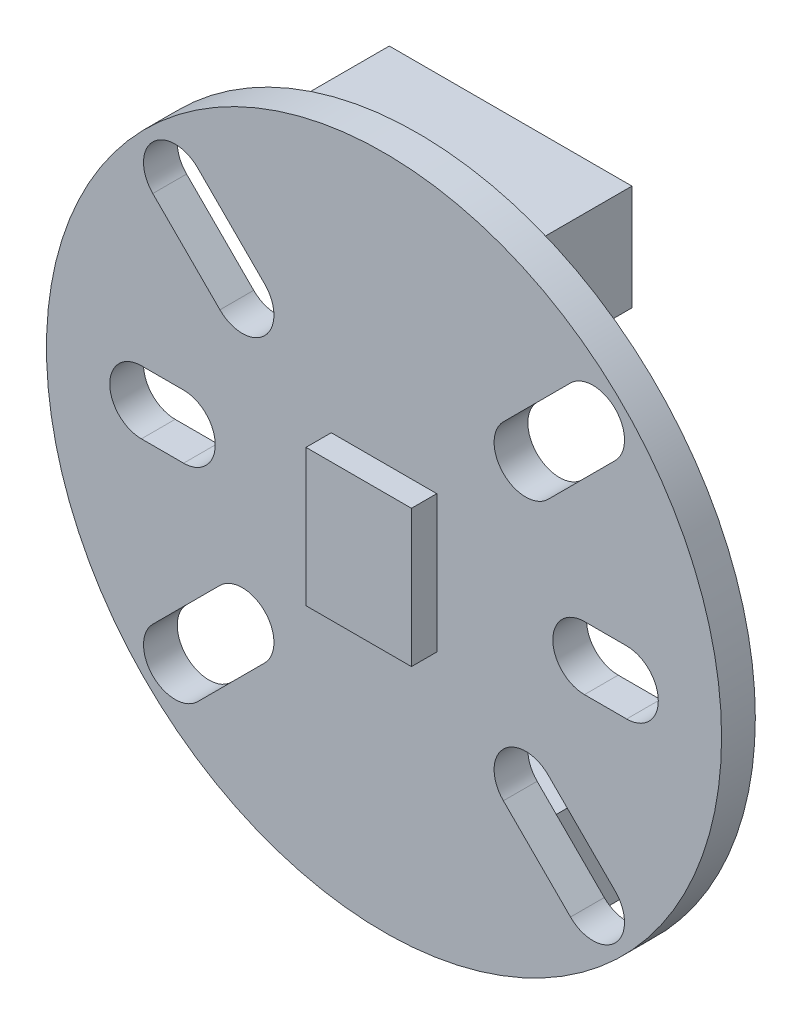
SolidWorks part; units mm, degrees
ref_plane "Front Plane" through (0, 0, 0) normal (0, 0, 1) x (1, 0, 0)
ref_plane "Top Plane" through (0, 0, 0) normal (0, 1, 0) x (1, 0, 0)
ref_plane "Right Plane" through (0, 0, 0) normal (1, 0, 0) x (0, 0, -1)
sketch "Sketch1" plane through (0, 0, 0) normal (0, 0, 1) x (1, 0, 0)
  circle A0 centre (0, 0) radius 16
  dimension "D1" = 32
extrude "Boss-Extrude1" add sketch "Sketch1" along normal blind 1.6
sketch "Sketch2" plane through (0, 0, 1.6) normal (0, 0, 1) x (1, 0, 0)
  line L1 (-2.5, 3.25) -> (2.5, 3.25)
  line L2 (-2.5, 3.25) -> (-2.5, -3.25)
  line L3 (-2.5, -3.25) -> (2.5, -3.25)
  line L4 (2.5, 3.25) -> (2.5, -3.25)
  line L5 (-2.5, 3.25) -> (2.5, -3.25) construction
  line L6 (-2.5, -3.25) -> (2.5, 3.25) construction
  point P0 (0, 0)
  dimension "D1" = 6.5
  dimension "D2" = 5
extrude "Boss-Extrude2" add sketch "Sketch2" along normal blind 1.2
sketch "Sketch3" plane through (0, 0, 1.6) normal (0, 0, 1) x (1, 0, 0)
  line L0 (0, 0) -> (-11.5, 0) construction
  line L1 (0, 0) -> (-6.7175, -6.7175) construction
  line L4 (-6.7175, -6.7175) -> (-9.8995, -9.8995) construction
  line L7 (-5.6569, -7.7782) -> (-8.8388, -10.9602)
  line L8 (-7.7782, -5.6569) -> (-10.9602, -8.8388)
  line L9 (-9.5, 0) -> (-11.5, 0) construction
  line L10 (-9.5, -1.5) -> (-11.5, -1.5)
  line L11 (-9.5, 1.5) -> (-11.5, 1.5)
  line L12 (-6.7175, 6.7175) -> (-9.8995, 9.8995) construction
  line L13 (-7.7782, 5.6569) -> (-10.9602, 8.8388)
  line L14 (-5.6569, 7.7782) -> (-8.8388, 10.9602)
  line L15 (6.7175, 6.7175) -> (9.8995, 9.8995) construction
  line L16 (5.6569, 7.7782) -> (8.8388, 10.9602)
  line L17 (7.7782, 5.6569) -> (10.9602, 8.8388)
  line L18 (6.7175, -6.7175) -> (9.8995, -9.8995) construction
  line L19 (7.7782, -5.6569) -> (10.9602, -8.8388)
  line L20 (5.6569, -7.7782) -> (8.8388, -10.9602)
  line L21 (9.5, 0) -> (11.5, 0) construction
  line L22 (9.5, 1.5) -> (11.5, 1.5)
  line L23 (9.5, -1.5) -> (11.5, -1.5)
  arc A6 (-5.6569, -7.7782) -> (-7.7782, -5.6569) centre (-6.7175, -6.7175) ccw
  arc A7 (-10.9602, -8.8388) -> (-8.8388, -10.9602) centre (-9.8995, -9.8995) ccw
  arc A8 (-9.5, -1.5) -> (-9.5, 1.5) centre (-9.5, 0) ccw
  arc A9 (-11.5, 1.5) -> (-11.5, -1.5) centre (-11.5, 0) ccw
  arc A11 (-7.7782, 5.6569) -> (-5.6569, 7.7782) centre (-6.7175, 6.7175) ccw
  arc A12 (-8.8388, 10.9602) -> (-10.9602, 8.8388) centre (-9.8995, 9.8995) ccw
  arc A13 (5.6569, 7.7782) -> (7.7782, 5.6569) centre (6.7175, 6.7175) ccw
  arc A14 (10.9602, 8.8388) -> (8.8388, 10.9602) centre (9.8995, 9.8995) ccw
  arc A15 (7.7782, -5.6569) -> (5.6569, -7.7782) centre (6.7175, -6.7175) ccw
  arc A16 (8.8388, -10.9602) -> (10.9602, -8.8388) centre (9.8995, -9.8995) ccw
  arc A17 (9.5, 1.5) -> (9.5, -1.5) centre (9.5, 0) ccw
  arc A18 (11.5, -1.5) -> (11.5, 1.5) centre (11.5, 0) ccw
  point P4 (-8.3085, -8.3085)
  point P14 (-10.5, 0)
  point P20 (0, 0)
  point P22 (-8.3085, 8.3085)
  point P29 (8.3085, 8.3085)
  point P36 (8.3085, -8.3085)
  point P43 (0, 0)
  point P45 (10.5, 0)
  point P50 (0, 0)
  dimension "D1" = 4
  dimension "D2" = 4.5
  dimension "D3" = 1.5
  dimension "D5" = 1.5
  dimension "D6" = 2
  dimension "D7" = 2
extrude "Cut-Extrude1" cut sketch "Sketch3" against normal through all
sketch "Sketch4" plane through (0, 0, 0) normal (0, 0, -1) x (-1, 0, 0)
  line L0 (0, 0) -> (0, 14.5) construction
  line L1 (0, 0) -> (0, -14.5) construction
  line L8 (5.75, 9.5) -> (-5.75, 9.5)
  line L9 (5.75, 9.5) -> (5.75, 14.5)
  line L10 (5.75, 14.5) -> (-5.75, 14.5)
  line L11 (-5.75, 9.5) -> (-5.75, 14.5)
  line L12 (5.75, 9.5) -> (-5.75, 14.5) construction
  line L13 (5.75, 14.5) -> (-5.75, 9.5) construction
  line L14 (5.75, -14.5) -> (-5.75, -14.5)
  line L15 (5.75, -14.5) -> (5.75, -9.5)
  line L16 (5.75, -9.5) -> (-5.75, -9.5)
  line L17 (-5.75, -14.5) -> (-5.75, -9.5)
  line L18 (5.75, -14.5) -> (-5.75, -9.5) construction
  line L19 (5.75, -9.5) -> (-5.75, -14.5) construction
  dimension "D1" = 14.5
  dimension "D2" = 14.5
  dimension "D3" = 14.5
  dimension "D5" = 5
  dimension "D6" = 11.5
  dimension "D8" = 14.5
  dimension "D9" = 2
extrude "Boss-Extrude3" add sketch "Sketch4" along normal blind 4.4
